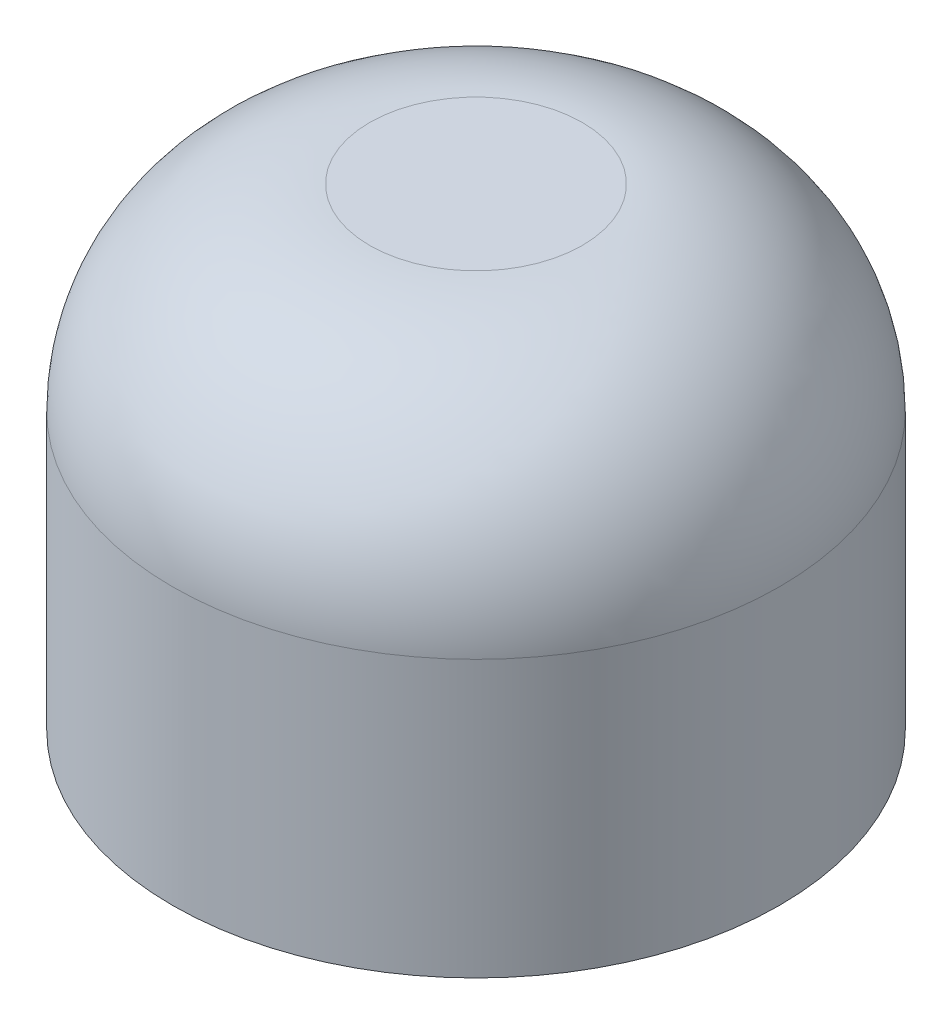
SolidWorks part; units mm, degrees
ref_plane "Front Plane" through (0, 0, 0) normal (0, 0, 1) x (1, 0, 0)
ref_plane "Top Plane" through (0, 0, 0) normal (0, 1, 0) x (1, 0, 0)
ref_plane "Right Plane" through (0, 0, 0) normal (1, 0, 0) x (0, 0, -1)
sketch "Sketch1" plane through (0, 0, 0) normal (0, 1, 0) x (1, 0, 0)
  circle A0 centre (0, 0) radius 1.925
  dimension "D1" = 3.85
extrude "Boss-Extrude1" add sketch "Sketch1" along normal blind 3
fillet "Fillet3" radius 1.25 1 edges at (0, 3, 1.925)
